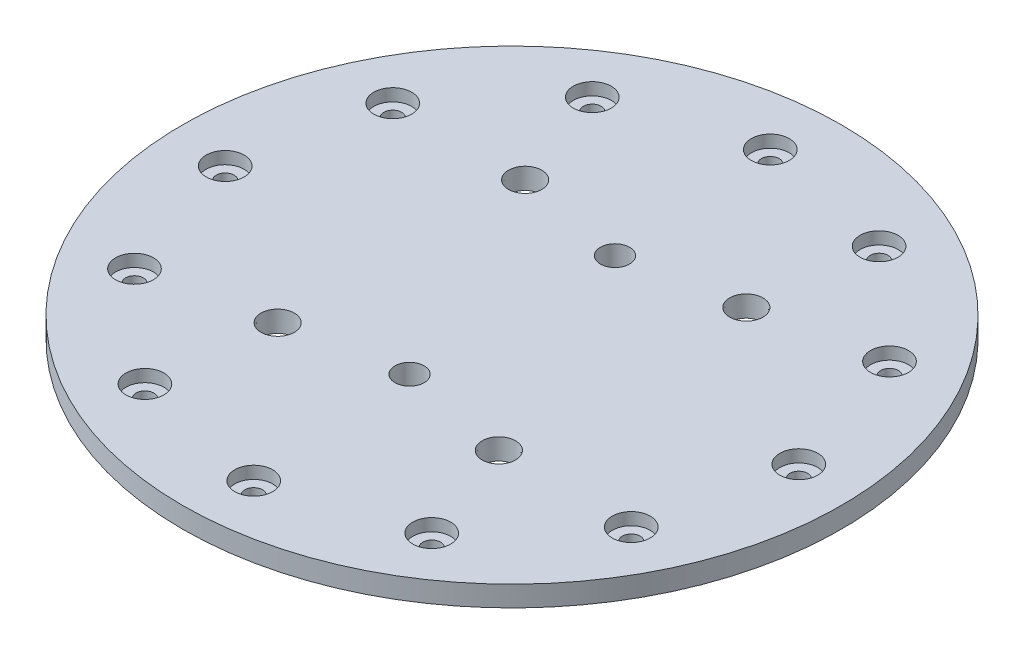
SolidWorks part; units mm, degrees
material "1023 Carbon Steel Sheet (SS)"
ref_plane "Front Plane" through (0, 0, 0) normal (0, 0, 1) x (1, 0, 0)
ref_plane "Top Plane" through (0, 0, 0) normal (0, 1, 0) x (1, 0, 0)
ref_plane "Right Plane" through (0, 0, 0) normal (1, 0, 0) x (0, 0, -1)
sketch "Sketch1" plane through (0, 0, 0) normal (0, 1, 0) x (1, 0, 0)
  line L0 (-90.5237, 46.1304) -> (-59.4062, 30.2731) construction
  line L1 (0, 0) -> (0, 97.5433) construction
  circle A0 centre (0, 0) radius 101.6
  circle A3 centre (0, 0) radius 84.1375 construction
  circle A4 centre (-74.965, 38.2017) radius 0.254
  point P7 (-74.965, 38.2017)
extrude "Boss-Extrude1" add sketch "Sketch1" along normal blind 6.35
hole_wizard "CBORE for M5 Hex Head Machine Screw1" positions "Sketch6" profile "Sketch7" counterbore size "M5" standard "ANSI Metric" end condition through all
sketch "Sketch6" plane through (0, 6.35, 0) normal (0, 1, 0) x (1, 0, 0)
  point P0 (-74.965, 38.2017)
sketch "Sketch7" plane through (-74.965, 6.35, -38.2017) normal (1, 0, 0) x (0, 0, 1)
  line L0 (0, 0) -> (0, 6.35)
  line L1 (0, 6.35) -> (2.75, 6.35)
  line L3 (2.75, 6.35) -> (2.75, 3.8)
  line L4 (2.75, 3.8) -> (5.855, 3.8)
  line L5 (5.855, 3.8) -> (5.855, 0)
  line L7 (5.855, 0) -> (0, 0)
  line L11 (0, -6.35) -> (0, 107.95) construction
  dimension "Thru Hole Dia." = 5.5
  dimension "Thru Hole Depth" = 6.35
  dimension "C'Bore Dia." = 11.71
  dimension "C'Bore Depth" = 3.8
pattern_circular "CirPattern1" count 12 over 360 about axis through (0, 0, 0) along (0, 1, 0) of "CBORE for M5 Hex Head Machine Screw1"
sketch "Sketch8" plane through (0, 6.35, 0) normal (0, 1, 0) x (1, 0, 0)
  line L0 (0, 0) -> (63.5, 0) construction
  line L1 (0, 0) -> (0, 63.5) construction
  line L2 (0, 0) -> (0, 31.75) construction
  line L3 (-34.0945, -38.1467) -> (34.0945, -38.1467) construction
  line L4 (-34.0945, -38.1467) -> (-34.0945, 38.1467) construction
  line L5 (-34.0945, 38.1467) -> (34.0945, 38.1467) construction
  line L6 (34.0945, -38.1467) -> (34.0945, 38.1467) construction
  line L7 (-34.0945, -38.1467) -> (34.0945, 38.1467) construction
  line L8 (-34.0945, 38.1467) -> (34.0945, -38.1467) construction
  line L9 (0, 0) -> (0, -31.5816) construction
  circle A0 centre (0, 0) radius 63.5 construction
  circle A1 centre (-34.0945, 38.1467) radius 1.6768
  circle A2 centre (34.0945, 38.1467) radius 1.9562
  circle A3 centre (34.0945, -38.1467) radius 1.9562
  circle A4 centre (-34.0945, -38.1467) radius 2.2357
  point P15 (0, 0)
hole_wizard "1/8 NPT Tapped Hole1" positions "3DSketch2" profile "Sketch10" size "1/8" standard "ANSI Inch" end condition through all
sketch3d "3DSketch2"
  point P0 (-34.0945, 6.35, -38.1467)
  point P3 (34.0945, 6.35, -38.1467)
  point P6 (34.0945, 6.35, 38.1467)
  point P9 (-34.0945, 6.35, 38.1467)
sketch "Sketch10" plane through (-34.0945, 6.35, -38.1467) normal (1, 0, 0) x (0, 0, 1)
  line L0 (0, 0) -> (0, 6.35)
  line L1 (0, 6.35) -> (4.2164, 6.35)
  line L2 (-4.9362, 6.858) -> (-5.1415, 0) construction
  line L3 (4.2164, 6.35) -> (4.2164, 6.858)
  line L4 (4.2164, 6.858) -> (4.9362, 6.858)
  line L5 (4.9362, 6.858) -> (5.1415, 0)
  line L7 (5.1415, 0) -> (0, 0)
  line L8 (0, -6.35) -> (0, 107.95) construction
  line L11 (-4.2164, 6.858) -> (-4.9362, 6.858) construction
  dimension "Thru Tap Drill Dia." = 8.4328
  dimension "Thru Tap Drill Depth" = 6.35
  dimension "Thread Dia." = 10.283
  dimension "Thread Angle" = 3.43
  dimension "Thread Depth" = 6.858
hole_wizard "M10x1.0 Tapped Hole1" positions "3DSketch3" profile "Sketch11" tap size "M10x1.0" standard "ANSI Metric"
sketch3d "3DSketch3"
  point P0 (0, 6.35, -31.75)
  point P3 (0, 6.35, 31.5816)
sketch "Sketch11" plane through (0, 6.35, -31.75) normal (1, 0, 0) x (0, 0, 1)
  line L0 (0, 0) -> (0, 27.8499)
  line L1 (0, 27.8499) -> (4.5, 25.146)
  line L2 (4.5, 25.146) -> (4.5, 0)
  line L5 (4.5, 0) -> (0, 0)
  line L10 (0, 27.8499) -> (-4.5, 25.146) construction
  line L11 (0, -6.35) -> (0, 107.95) construction
  dimension "Tap Drill Dia." = 9
  dimension "Tap Drill Depth" = 25.146
  dimension "Drill Angle" = 118
cosmetic thread "Hole Thread1" parameters "D1"=6.35, "D2"=10
cosmetic thread "Hole Thread2" parameters "D1"=6.35, "D2"=10
